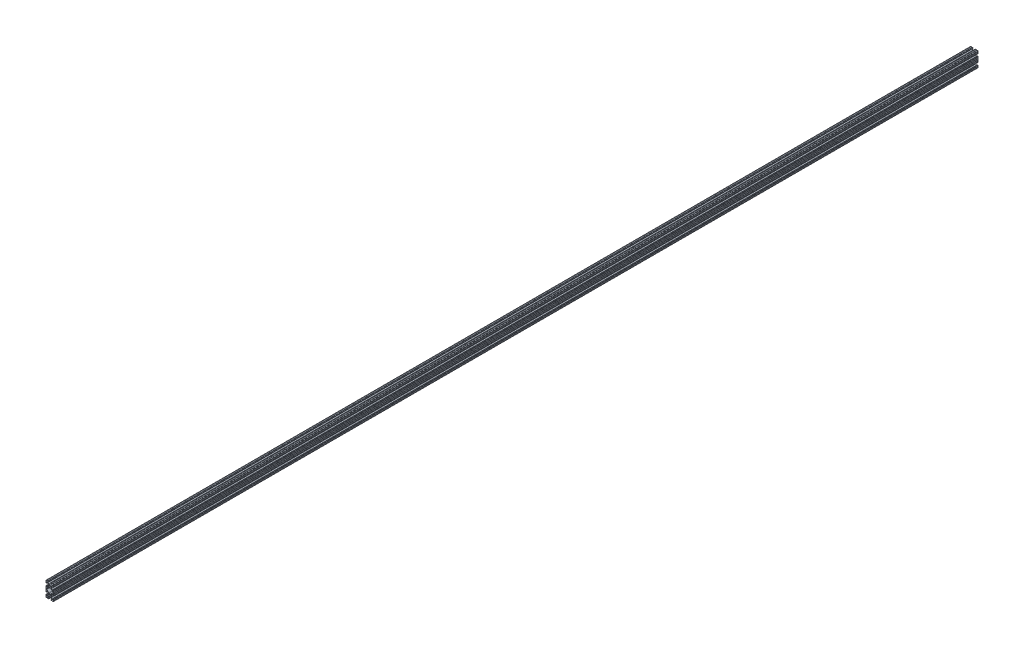
SolidWorks part; units mm, degrees
ref_plane "Front Plane" through (0, 0, 0) normal (0, 0, 1) x (1, 0, 0)
ref_plane "Top Plane" through (0, 0, 0) normal (0, 1, 0) x (1, 0, 0)
ref_plane "Right Plane" through (0, 0, 0) normal (1, 0, 0) x (0, 0, -1)
sketch "Sketch2" plane through (0, 0, 0) normal (0, 0, 1) x (1, 0, 0)
  line L0 (0, 25.4) -> (0, -25.4) construction
  line L1 (-12.7, 0) -> (12.7, 0) construction
  line L2 (3.2512, -25.4) -> (12.7, -25.4)
  line L3 (12.7, -25.4) -> (12.7, -15.9512)
  line L4 (3.2512, -25.4) -> (3.2512, -23.1902)
  line L5 (3.2512, -23.1902) -> (8.9276, -23.1902)
  line L6 (8.9276, -23.1902) -> (3.0856, -17.3482)
  line L7 (0, -12.7) -> (12.7, -25.4) construction
  line L8 (12.7, -15.9512) -> (10.4902, -15.9512)
  line L9 (10.4902, -15.9512) -> (10.4902, -21.6276)
  line L10 (10.4902, -21.6276) -> (4.6482, -15.7856)
  line L11 (3.2512, -25.4) -> (0, -25.4) construction
  line L12 (0, -25.4) -> (-3.2512, -25.4) construction
  line L13 (-3.2512, -25.4) -> (-12.7, -25.4) construction
  line L14 (12.7, 25.4) -> (-12.7, 25.4) construction
  line L15 (0, 12.7) -> (0, -12.7) construction
  circle A0 centre (0, -12.7) radius 2.6035
  arc A1 (6.3485, -23.1902) -> (7.1039, -21.3665) centre (6.3485, -22.1219) ccw construction
  point P8 (0, -17.3482)
  point P16 (-2.6035, -12.7)
  point P18 (2.6035, -12.7)
  point P19 (0, -10.0965)
  point P20 (0, -15.3035)
  point P27 (-12.7, -25.4)
  point P30 (0, 25.4)
  point P31 (12.7, 25.4)
  point P32 (-12.7, 25.4)
  point P33 (12.7, -25.4)
  point P34 (0, -12.7)
  point P35 (0, 12.7)
  point P37 (0, 0)
  point P38 (-3.2512, -25.4)
  point P39 (3.2512, -25.4)
  dimension "Center Hole Diameter" = 5.207
  dimension "Rail Height" = 50.8
  dimension "Rail Width" = 25.4
  dimension "T-Slot Width" = 6.5024
  dimension "Slot Inner Width" = 14.8336
  dimension "Thickness" = 2.2098
  dimension "Slot Depth" = 5.842
  dimension "D1" = 2.2098
  dimension "C to C" = 25.4
sketch "Sketch3" plane through (0, 0, 0) normal (1, 0, 0) x (0, 0, -1)
  line L0 (-1524, -25.4) -> (1524, -25.4) construction
  line L1 (-1473.2, 0) -> (1473.2, 0) construction
  point P6 (-1524, -25.4)
  point P8 (-1473.2, 0)
  point P9 (1473.2, 0)
  point P10 (1524, -25.4)
  dimension "Length" = 3048
  dimension "D1" = 50.8
sketch "Sketch4" plane through (0, 0, 0) normal (0, 0, 1) x (1, 0, 0)
  line L0 (4.1904, -25.4) -> (10.1173, -25.4)
  line L1 (3.2512, -25.4) -> (12.7, -25.4) construction
  line L2 (3.2512, -25.4) -> (3.2512, -23.1902) construction
  line L3 (3.2512, -23.1902) -> (8.9276, -23.1902) construction
  line L4 (3.2512, -24.1294) -> (3.2512, -24.4608)
  line L5 (4.1904, -23.1902) -> (6.3485, -23.1902)
  line L6 (0, -17.3482) -> (2.164, -17.3482)
  line L7 (8.9276, -23.1902) -> (3.0856, -17.3482) construction
  line L8 (3.7373, -17.9999) -> (7.1039, -21.3665)
  line L9 (12.7, -25.4) -> (12.7, -15.9512) construction
  line L10 (10.4902, -21.6276) -> (4.6482, -15.7856) construction
  line L11 (10.4902, -15.9512) -> (10.4902, -21.6276) construction
  line L12 (10.4902, -19.0485) -> (10.4902, -16.8904)
  line L13 (12.7, -15.9512) -> (10.4902, -15.9512) construction
  line L14 (11.4294, -15.9512) -> (11.7608, -15.9512)
  line L15 (12.7, -16.8904) -> (12.7, -22.8173)
  line L16 (8.6665, -19.8039) -> (5.2999, -16.4373)
  line L17 (4.6482, -12.7) -> (4.6482, -14.864)
  line L19 (0, -17.3482) -> (0, -15.3035)
  line L20 (0, 25.4) -> (0, -25.4) construction
  line L21 (4.6482, -12.7) -> (2.6035, -12.7)
  arc A0 (3.2512, -24.4608) -> (4.1904, -25.4) centre (4.1904, -24.4608) ccw
  circle A1 centre (0, -12.7) radius 2.6035 construction
  arc A2 (3.2512, -24.1294) -> (4.1904, -23.1902) centre (4.1904, -24.1294) cw
  arc A3 (6.3485, -23.1902) -> (7.1039, -21.3665) centre (6.3485, -22.1219) ccw
  arc A4 (2.164, -17.3482) -> (3.7373, -17.9999) centre (2.164, -19.5732) cw
  arc A5 (10.1173, -25.4) -> (12.7, -22.8173) centre (10.1173, -22.8173) ccw
  arc A6 (8.6665, -19.8039) -> (10.4902, -19.0485) centre (9.4219, -19.0485) ccw
  arc A7 (10.4902, -16.8904) -> (11.4294, -15.9512) centre (11.4294, -16.8904) cw
  arc A8 (11.7608, -15.9512) -> (12.7, -16.8904) centre (11.7608, -16.8904) cw
  arc A9 (5.2999, -16.4373) -> (4.6482, -14.864) centre (6.8732, -14.864) cw
  arc A11 (0, -15.3035) -> (2.6035, -12.7) centre (0, -12.7) ccw
  dimension "D1" = 2.5827
  dimension "D2" = 2.225
  dimension "D3" = 0.9392
extrude "Boss-Extrude1" add sketch "Sketch4" along normal mid plane 3048
sketch "Sketch5" plane through (0, 0, 0) normal (0, 0, 1) x (1, 0, 0)
  line L0 (3.2512, -25.4) -> (12.7, -25.4) construction
  line L1 (4.1904, -23.1902) -> (6.3485, -23.1902) construction
  line L3 (0, -12.7) -> (12.7, -25.4) construction
  line L4 (6.3485, -23.1902) -> (6.3485, -25.4) construction
  line L5 (8.9276, -23.1902) -> (3.0856, -17.3482) construction
  circle A0 centre (10.3562, -25.4) radius 0.5524
  circle A1 centre (5.796, -25.4) radius 0.5524
  circle A2 centre (12.7, -23.0562) radius 0.5524
  circle A3 centre (12.7, -18.496) radius 0.5524
  point P10 (5.2694, -23.1902)
  point P12 (9.4219, -19.0485)
  dimension "D1" = 1.1049
extrude "Cut-Extrude1" cut sketch "Sketch5" against normal through all both and the other way through all
mirror "Mirror1" about plane through (4.6482, -12.7, 1524) normal (0, -1, 0) of bodies 137 134
sketch "Sketch6" plane through (0, 0, 0) normal (0, 0, 1) x (1, 0, 0)
  line L0 (12.7, -1.7914) -> (12.7, 0)
  line L1 (12.7, 0) -> (9.8037, 0)
  line L2 (-12.7, 0) -> (12.7, 0) construction
  line L3 (9.8037, 0) -> (9.8037, -2.3438)
  line L4 (9.8037, -2.3438) -> (12.1476, -2.3438)
  circle A0 centre (12.7, -2.3438) radius 0.5524 construction
  arc A1 (12.7, -1.7914) -> (12.1476, -2.3438) centre (12.7, -2.3438) ccw
  arc A4 (12.58, -1.8046) -> (12.7, -2.8963) centre (12.7, -2.3438) ccw construction
  arc A6 (9.8037, 0) -> (10.8954, -0.12) centre (10.3562, 0) ccw construction
extrude "Boss-Extrude2" add sketch "Sketch6" along normal mid plane 3048
sketch "Sketch7" plane through (0, 0, 0) normal (0, 0, 1) x (1, 0, 0)
  line L0 (5.4206, -5.7168) -> (10.3284, -0.809)
  line L1 (3.7373, -7.4001) -> (7.1039, -4.0335) construction
  line L2 (10.4902, -0.4184) -> (10.4902, 0)
  line L3 (0, 0) -> (10.4902, 0)
  line L4 (-12.7, 0) -> (12.7, 0) construction
  line L5 (0, 0) -> (5.4206, -5.7168)
  arc A0 (10.3284, -0.809) -> (10.4902, -0.4184) centre (9.9377, -0.4184) ccw
  arc A3 (12.7, -1.7914) -> (12.7, -2.8963) centre (12.7, -2.3438) ccw construction
extrude "Cut-Extrude2" cut sketch "Sketch7" against normal through all both and the other way through all
mirror "Mirror2" about plane through (0, 0, 0) normal (0, 1, 0) of bodies 139 135
mirror "Mirror3" about plane through (0, 0, 0) normal (1, 0, 0) of bodies 136
sketch "Sketch10" plane through (0, 0, 1524) normal (0, 0, 1) x (1, 0, 0)
  line L1 (-42.2812, 28.0763) -> (45.3909, 28.0763)
  line L2 (-42.2812, 28.0763) -> (-42.2812, -37.0211)
  line L3 (-42.2812, -37.0211) -> (45.3909, -37.0211)
  line L4 (45.3909, 28.0763) -> (45.3909, -37.0211)
equation "\"D1@Boss-Extrude1\"=\"Length@Sketch3\""
equation "\"D1@Sketch2\"=\"Thickness@Sketch2\""
equation "\"D2@Sketch4\"=\"Slot Inner Width@Sketch2\"*0.15"
equation "\"D1@Sketch4\"=\"D3@Sketch4\"*2.75"
equation "\"D3@Sketch4\"=\"Thickness@Sketch2\"*0.425"
equation "\"D1@Sketch5\"=\"Thickness@Sketch2\"*0.5"
equation "\"D1@Boss-Extrude2\"=\"Length@Sketch3\""
